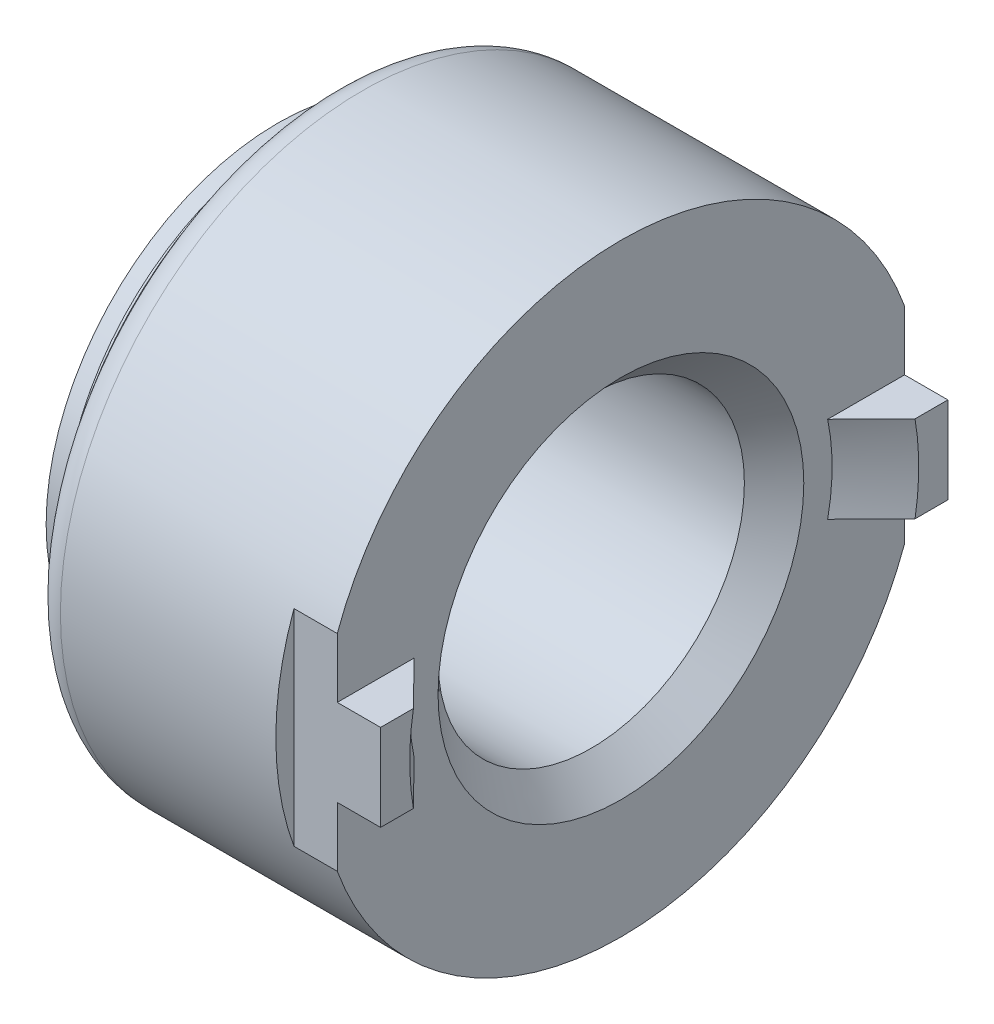
SolidWorks part; units mm, degrees
ref_plane "Face" through (0, 0, 0) normal (0, 0, 1) x (1, 0, 0)
ref_plane "Dessus" through (0, 0, 0) normal (0, 1, 0) x (1, 0, 0)
ref_plane "Droite" through (0, 0, 0) normal (1, 0, 0) x (0, 0, -1)
sketch "Esquisse1" plane through (0, 0, 0) normal (0, 0, 1) x (1, 0, 0)
  line L0 (1.48, 8.25) -> (1.48, 0)
  line L1 (1.48, 0) -> (9.38, 0)
  line L2 (9.38, 0) -> (9.38, 8.25)
  line L3 (9.38, 8.25) -> (1.48, 8.25)
  line L4 (1.48, 0) -> (9.38, 0) construction
revolve "Révolution1" add sketch "Esquisse1" angle 360 about L4
sketch "Esquisse2" plane through (9.38, 0, 0) normal (1, 0, 0) x (0, 0, -1)
  line L0 (-5.6523, -1.184) -> (-7.755, -1.184)
  line L1 (-7.755, -1.184) -> (-7.755, 1.184)
  line L2 (-7.755, 1.184) -> (-5.6523, 1.184)
  arc A0 (-5.6523, 1.184) -> (-5.6523, -1.184) centre (0, 0) ccw
extrude "Boss.-Extru.1" add sketch "Esquisse2" along normal blind 1.184
ref_plane "Plan1" through (9.38, 0, 0) normal (1, 0, 0) x (0, 0, -1)
ref_plane "Plan2" through (8.195, 0, 0) normal (-1, 0, 0) x (0, -1, 0)
sketch "Esquisse4" plane through (8.195, 0, 0) normal (-1, 0, 0) x (0, -1, 0)
  line L0 (-2.8147, 7.755) -> (2.8147, 7.755)
  arc A0 (2.8147, 7.755) -> (-2.8147, 7.755) centre (0, 0) ccw
extrude "Enlèv. mat.-Extru.1" cut sketch "Esquisse4" against normal up to surface up to plane "Plan1"
sketch "Esquisse5" plane through (9.38, 0, 0) normal (1, 0, 0) x (0, 0, -1)
  line L0 (7.755, 1.184) -> (7.755, -1.184)
  line L1 (7.755, -1.184) -> (5.6523, -1.184)
  line L2 (5.6523, 1.184) -> (7.755, 1.184)
  arc A0 (5.6523, -1.184) -> (5.6523, 1.184) centre (0, 0) ccw
extrude "Boss.-Extru.2" add sketch "Esquisse5" along normal blind 1.184
sketch "Esquisse7" plane through (8.195, 0, 0) normal (-1, 0, 0) x (0, -1, 0)
  line L0 (2.8147, -7.755) -> (-2.8147, -7.755)
  arc A0 (-2.8147, -7.755) -> (2.8147, -7.755) centre (0, 0) ccw
extrude "Enlèv. mat.-Extru.2" cut sketch "Esquisse7" against normal up to surface up to plane "Plan1"
sketch "Esquisse8" plane through (1.48, 0, 0) normal (-1, 0, 0) x (0, 0, 1)
  circle A0 centre (0, 0) radius 7.2925
extrude "Boss.-Extru.3" add sketch "Esquisse8" along normal blind 0.296
sketch "Esquisse9" plane through (1.184, 0, 0) normal (-1, 0, 0) x (0, 0, 1)
  circle A0 centre (0, 0) radius 6.1088
extrude "Boss.-Extru.4" add sketch "Esquisse9" along normal blind 0.74 draft 17.001 draft outward yes
sketch "Esquisse10" plane through (0.444, 0, 0) normal (-1, 0, 0) x (0, 0, 1)
  circle A0 centre (0, 0) radius 6.335
extrude "Boss.-Extru.5" add sketch "Esquisse10" along normal blind 0.444
draft "Dépouille1" type of draft neutral plane draft angle 45 faces to draft 2 face at (9.972, 0, 5.7137) face at (9.972, 0, -5.7137) neutral plane through (9.38, 0, 0) neutral plane normal (1, 0, 0) parameters "D1"=45
hole_wizard "Perçage1" positions "Esquisse12" profile "Esquisse11" legacy
sketch "Esquisse12" plane through (9.38, 0, 0) normal (1, 0, 0) x (0, 0, -1)
  point P0 (0, 0)
sketch "Esquisse11" plane through (9.38, 0, 0) normal (0, 1, 0) x (0, 0, -1)
  line L0 (0, 0) -> (0, 9.38)
  line L1 (0, 9.38) -> (4.188, 9.38)
  line L2 (4.188, 9.38) -> (4.188, 0)
  line L3 (4.188, 0) -> (0, 0)
  line L4 (0, 110) -> (0, -10) construction
  dimension "Diamètre" = 8.376
  dimension "Profondeur" = 9.38
chamfer "Chanfrein1" distance 0.812 angle 45 2 edges at (0, 0, -4.188) (9.38, 0, -4.188)
fillet "Congé1" radius 0.825 1 edges at (1.48, 0, -8.25)
